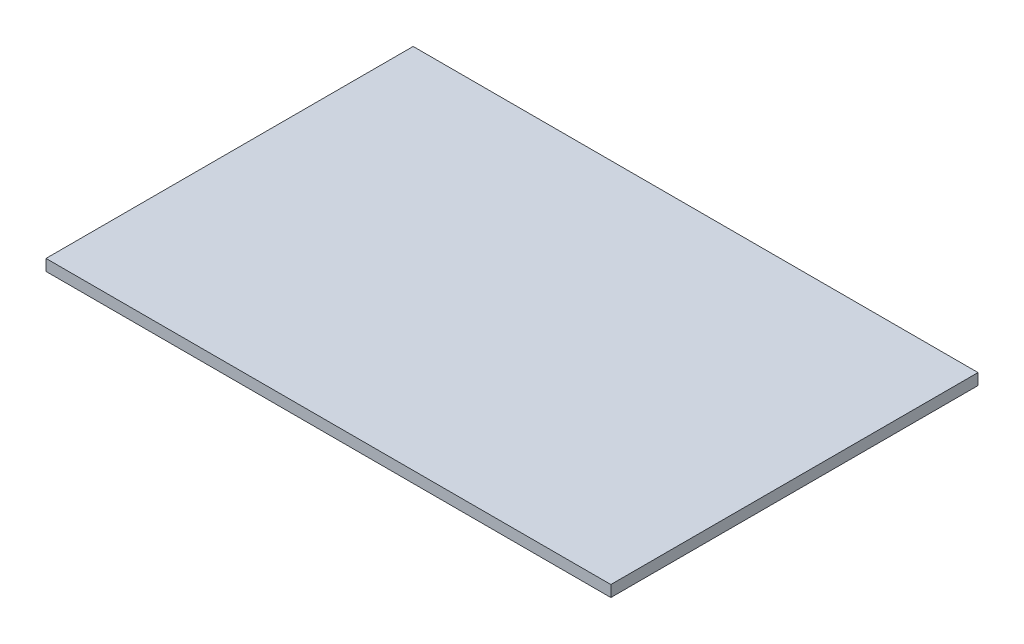
SolidWorks part; units mm, degrees
material "Bordo"
ref_plane "Plano frontal" through (0, 0, 0) normal (0, 0, 1) x (1, 0, 0)
ref_plane "Plano superior" through (0, 0, 0) normal (0, 1, 0) x (1, 0, 0)
ref_plane "Plano direito" through (0, 0, 0) normal (1, 0, 0) x (0, 0, -1)
sketch "Esboço1" plane through (0, 0, 0) normal (0, 1, 0) x (1, 0, 0)
  line L1 (-100, -65) -> (100, -65)
  line L2 (-100, -65) -> (-100, 65)
  line L3 (-100, 65) -> (100, 65)
  line L4 (100, -65) -> (100, 65)
  line L5 (-100, -65) -> (100, 65) construction
  line L6 (-100, 65) -> (100, -65) construction
  point P0 (0, 0)
  dimension "D1" = 200
  dimension "D2" = 130
extrude "Ressalto-extrusão1" add sketch "Esboço1" along normal blind 4
